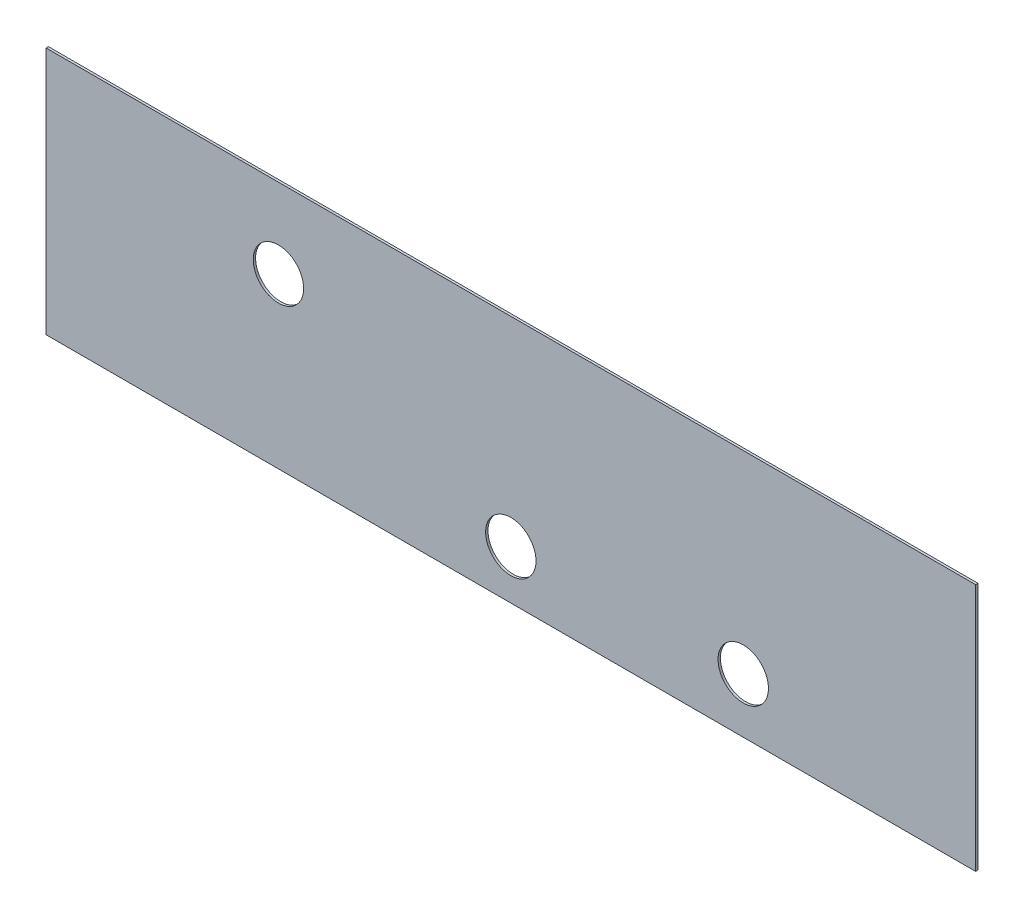
SolidWorks part; units mm, degrees
ref_plane "Front Plane" through (0, 0, 0) normal (0, 0, 1) x (1, 0, 0)
ref_plane "Top Plane" through (0, 0, 0) normal (0, 1, 0) x (1, 0, 0)
ref_plane "Right Plane" through (0, 0, 0) normal (1, 0, 0) x (0, 0, -1)
sketch "Sketch1" plane through (0, 0, 0) normal (0, 0, 1) x (1, 0, 0)
  line L0 (0, 0) -> (0, 105.5)
  line L1 (0, 105.5) -> (394.92, 105.5)
  line L2 (394.92, 105.5) -> (394.92, 0)
  line L3 (394.92, 0) -> (0, 0)
  line L4 (197.46, 0) -> (197.46, 20.8) construction
  line L5 (0, 52.75) -> (197.46, 52.75) construction
  line L6 (98.73, 0) -> (98.73, 71.7) construction
  line L7 (197.46, 52.75) -> (394.92, 52.75) construction
  line L8 (296.19, 0) -> (296.19, 23.3) construction
  circle A0 centre (197.46, 20.8) radius 10.7
  circle A1 centre (98.73, 71.7) radius 10.7
  circle A2 centre (296.19, 23.3) radius 10.7
  dimension "D4" = 71.7
  dimension "D5" = 23.3
  dimension "D1" = 105.5
  dimension "D2" = 394.92
  dimension "D3" = 20.8
extrude "Boss-Extrude1" add sketch "Sketch1" along normal blind 1
